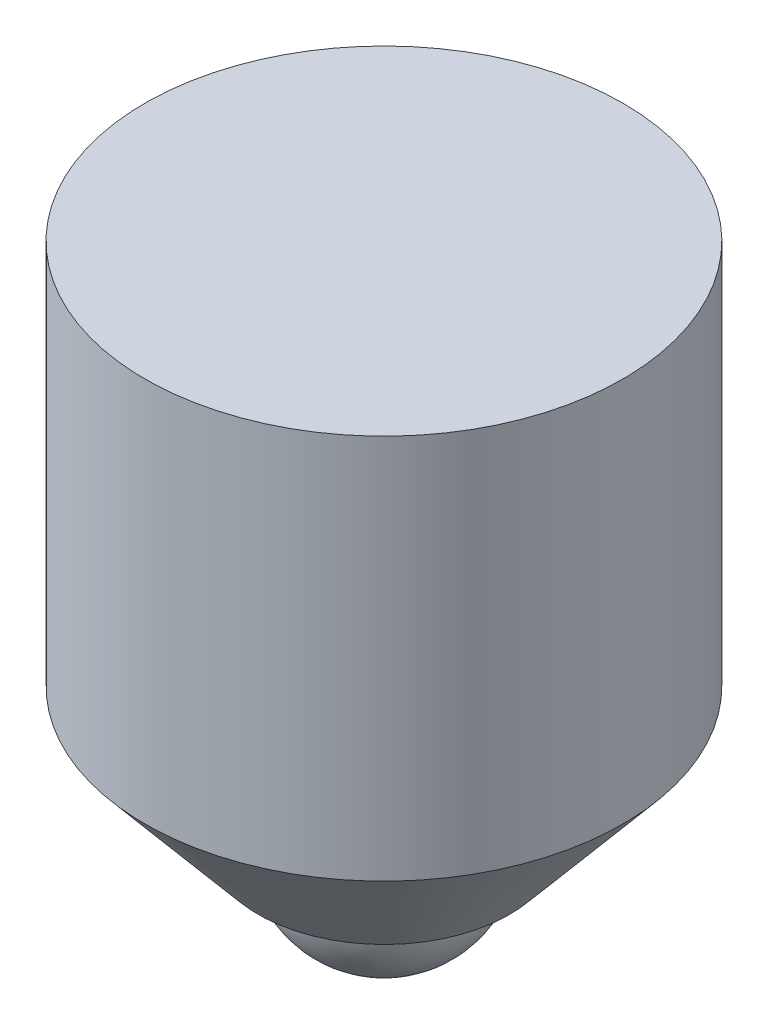
SolidWorks part; units mm, degrees
ref_plane "Front Plane" through (0, 0, 0) normal (0, 0, 1) x (1, 0, 0)
ref_plane "Top Plane" through (0, 0, 0) normal (0, 1, 0) x (1, 0, 0)
ref_plane "Right Plane" through (0, 0, 0) normal (1, 0, 0) x (0, 0, -1)
sketch "Sketch1" plane through (0, 0, 0) normal (1, 0, 0) x (0, 0, -1)
  line L0 (0, 0) -> (0, 3.2) construction
  line L1 (-0.5, 0.5) -> (-0.6527, 0.5)
  line L2 (-0.6527, 0.5) -> (-1.2401, 1.2)
  line L3 (-1.2401, 1.2) -> (-1.2401, 3.2)
  line L4 (-1.2401, 3.2) -> (0, 3.2)
  line L5 (0, 0) -> (0, 3.2)
  arc A0 (-0.5, 0.5) -> (0, 0) centre (0, 0.5) ccw
  dimension "D2" = 1
  dimension "D1" = 3.2
  dimension "D3" = 2
  dimension "D4" = 140
revolve "Revolve1" add sketch "Sketch1" angle 360 about L0
